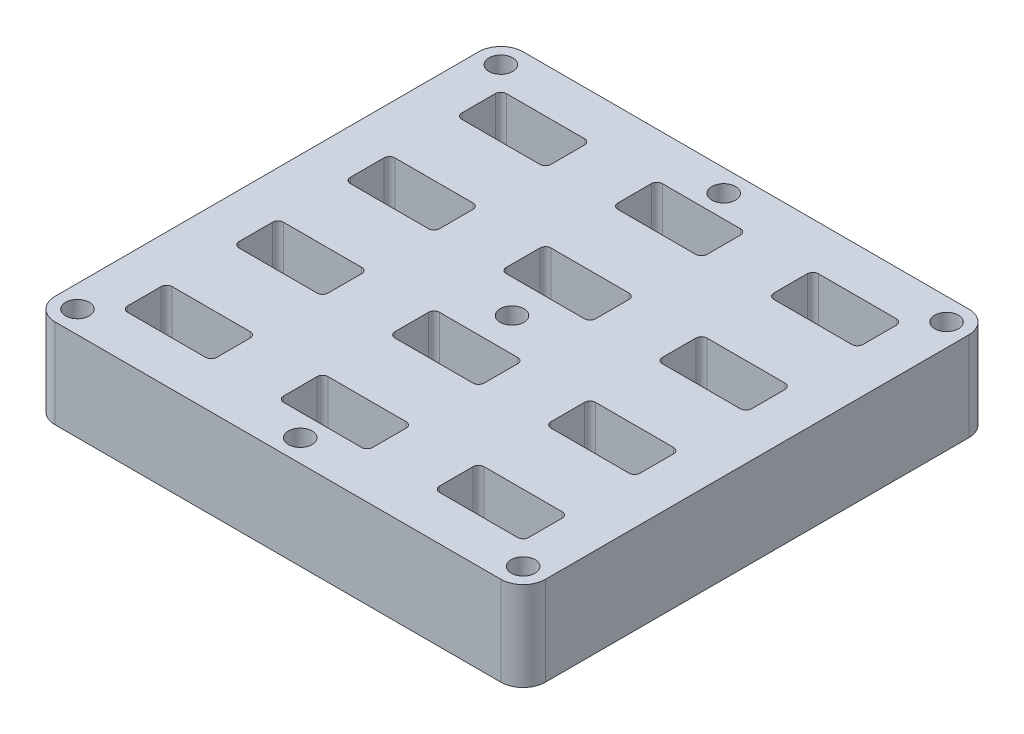
SolidWorks part; units mm, degrees
material "1060 Alloy"
ref_plane "Front" through (0, 0, 0) normal (0, 0, 1) x (1, 0, 0)
ref_plane "Top" through (0, 0, 0) normal (0, 1, 0) x (1, 0, 0)
ref_plane "Right" through (0, 0, 0) normal (1, 0, 0) x (0, 0, -1)
sketch "Sketch1" plane through (0, 0, 0) normal (0, 1, 0) x (1, 0, 0)
  line L1 (-63.5, -66.675) -> (63.5, -66.675)
  line L2 (-69.85, -60.325) -> (-69.85, 60.325)
  line L3 (-63.5, 66.675) -> (63.5, 66.675)
  line L4 (69.85, -60.325) -> (69.85, 60.325)
  line L5 (-69.85, -66.675) -> (69.85, 66.675) construction
  line L6 (-69.85, 66.675) -> (69.85, -66.675) construction
  line L7 (-55.5625, 41.275) -> (-33.3375, 41.275)
  line L8 (-57.15, 42.8625) -> (-57.15, 52.3875)
  line L9 (-55.5625, 53.975) -> (-33.3375, 53.975)
  line L10 (-31.75, 42.8625) -> (-31.75, 52.3875)
  line L11 (-57.15, 41.275) -> (-31.75, 53.975) construction
  line L12 (-57.15, 53.975) -> (-31.75, 41.275) construction
  line L16 (-12.7, 42.8625) -> (-12.7, 52.3875)
  line L17 (-11.1125, 41.275) -> (11.1125, 41.275)
  line L22 (12.7, 42.8625) -> (12.7, 52.3875)
  line L23 (-11.1125, 53.975) -> (11.1125, 53.975)
  line L28 (31.75, 42.8625) -> (31.75, 52.3875)
  line L29 (33.3375, 41.275) -> (55.5625, 41.275)
  line L110 (57.15, 42.8625) -> (57.15, 52.3875)
  line L111 (33.3375, 53.975) -> (55.5625, 53.975)
  line L196 (-57.15, 11.1125) -> (-57.15, 20.6375)
  line L197 (-55.5625, 9.525) -> (-33.3375, 9.525)
  line L198 (-31.75, 11.1125) -> (-31.75, 20.6375)
  line L199 (-55.5625, 22.225) -> (-33.3375, 22.225)
  line L200 (-12.7, 11.1125) -> (-12.7, 20.6375)
  line L201 (-11.1125, 22.225) -> (11.1125, 22.225)
  line L202 (12.7, 11.1125) -> (12.7, 20.6375)
  line L203 (-11.1125, 9.525) -> (11.1125, 9.525)
  line L204 (31.75, 11.1125) -> (31.75, 20.6375)
  line L205 (33.3375, 22.225) -> (55.5625, 22.225)
  line L206 (57.15, 11.1125) -> (57.15, 20.6375)
  line L207 (33.3375, 9.525) -> (55.5625, 9.525)
  line L212 (-57.15, -20.6375) -> (-57.15, -11.1125)
  line L213 (-55.5625, -22.225) -> (-33.3375, -22.225)
  line L214 (-31.75, -20.6375) -> (-31.75, -11.1125)
  line L215 (-55.5625, -9.525) -> (-33.3375, -9.525)
  line L216 (-12.7, -20.6375) -> (-12.7, -11.1125)
  line L217 (-11.1125, -9.525) -> (11.1125, -9.525)
  line L218 (12.7, -20.6375) -> (12.7, -11.1125)
  line L219 (-11.1125, -22.225) -> (11.1125, -22.225)
  line L220 (31.75, -20.6375) -> (31.75, -11.1125)
  line L221 (33.3375, -9.525) -> (55.5625, -9.525)
  line L222 (57.15, -20.6375) -> (57.15, -11.1125)
  line L223 (33.3375, -22.225) -> (55.5625, -22.225)
  line L228 (-57.15, -52.3875) -> (-57.15, -42.8625)
  line L229 (-55.5625, -53.975) -> (-33.3375, -53.975)
  line L230 (-31.75, -52.3875) -> (-31.75, -42.8625)
  line L231 (-55.5625, -41.275) -> (-33.3375, -41.275)
  line L232 (-12.7, -52.3875) -> (-12.7, -42.8625)
  line L233 (-11.1125, -41.275) -> (11.1125, -41.275)
  line L234 (12.7, -52.3875) -> (12.7, -42.8625)
  line L235 (-11.1125, -53.975) -> (11.1125, -53.975)
  line L236 (31.75, -52.3875) -> (31.75, -42.8625)
  line L237 (33.3375, -41.275) -> (55.5625, -41.275)
  line L238 (57.15, -52.3875) -> (57.15, -42.8625)
  line L239 (33.3375, -53.975) -> (55.5625, -53.975)
  arc A0 (-55.5625, 41.275) -> (-57.15, 42.8625) centre (-55.5625, 42.8625) cw
  arc A1 (-33.3375, 41.275) -> (-31.75, 42.8625) centre (-33.3375, 42.8625) ccw
  arc A2 (-33.3375, 53.975) -> (-31.75, 52.3875) centre (-33.3375, 52.3875) cw
  arc A3 (-55.5625, 53.975) -> (-57.15, 52.3875) centre (-55.5625, 52.3875) ccw
  arc A4 (-11.1125, 53.975) -> (-12.7, 52.3875) centre (-11.1125, 52.3875) ccw
  arc A5 (-11.1125, 41.275) -> (-12.7, 42.8625) centre (-11.1125, 42.8625) cw
  arc A6 (11.1125, 41.275) -> (12.7, 42.8625) centre (11.1125, 42.8625) ccw
  arc A7 (11.1125, 53.975) -> (12.7, 52.3875) centre (11.1125, 52.3875) cw
  arc A8 (33.3375, 53.975) -> (31.75, 52.3875) centre (33.3375, 52.3875) ccw
  arc A9 (33.3375, 41.275) -> (31.75, 42.8625) centre (33.3375, 42.8625) cw
  arc A10 (55.5625, 41.275) -> (57.15, 42.8625) centre (55.5625, 42.8625) ccw
  arc A11 (55.5625, 53.975) -> (57.15, 52.3875) centre (55.5625, 52.3875) cw
  arc A96 (-55.5625, 22.225) -> (-57.15, 20.6375) centre (-55.5625, 20.6375) ccw
  arc A97 (-55.5625, 9.525) -> (-57.15, 11.1125) centre (-55.5625, 11.1125) cw
  arc A98 (-33.3375, 9.525) -> (-31.75, 11.1125) centre (-33.3375, 11.1125) ccw
  arc A99 (-33.3375, 22.225) -> (-31.75, 20.6375) centre (-33.3375, 20.6375) cw
  arc A100 (-11.1125, 22.225) -> (-12.7, 20.6375) centre (-11.1125, 20.6375) ccw
  arc A101 (11.1125, 22.225) -> (12.7, 20.6375) centre (11.1125, 20.6375) cw
  arc A102 (11.1125, 9.525) -> (12.7, 11.1125) centre (11.1125, 11.1125) ccw
  arc A103 (-11.1125, 9.525) -> (-12.7, 11.1125) centre (-11.1125, 11.1125) cw
  arc A104 (33.3375, 22.225) -> (31.75, 20.6375) centre (33.3375, 20.6375) ccw
  arc A105 (55.5625, 22.225) -> (57.15, 20.6375) centre (55.5625, 20.6375) cw
  arc A106 (55.5625, 9.525) -> (57.15, 11.1125) centre (55.5625, 11.1125) ccw
  arc A107 (33.3375, 9.525) -> (31.75, 11.1125) centre (33.3375, 11.1125) cw
  arc A112 (-55.5625, -9.525) -> (-57.15, -11.1125) centre (-55.5625, -11.1125) ccw
  arc A113 (-55.5625, -22.225) -> (-57.15, -20.6375) centre (-55.5625, -20.6375) cw
  arc A114 (-33.3375, -22.225) -> (-31.75, -20.6375) centre (-33.3375, -20.6375) ccw
  arc A115 (-33.3375, -9.525) -> (-31.75, -11.1125) centre (-33.3375, -11.1125) cw
  arc A116 (-11.1125, -9.525) -> (-12.7, -11.1125) centre (-11.1125, -11.1125) ccw
  arc A117 (11.1125, -9.525) -> (12.7, -11.1125) centre (11.1125, -11.1125) cw
  arc A118 (11.1125, -22.225) -> (12.7, -20.6375) centre (11.1125, -20.6375) ccw
  arc A119 (-11.1125, -22.225) -> (-12.7, -20.6375) centre (-11.1125, -20.6375) cw
  arc A120 (33.3375, -9.525) -> (31.75, -11.1125) centre (33.3375, -11.1125) ccw
  arc A121 (55.5625, -9.525) -> (57.15, -11.1125) centre (55.5625, -11.1125) cw
  arc A122 (55.5625, -22.225) -> (57.15, -20.6375) centre (55.5625, -20.6375) ccw
  arc A123 (33.3375, -22.225) -> (31.75, -20.6375) centre (33.3375, -20.6375) cw
  arc A128 (-55.5625, -41.275) -> (-57.15, -42.8625) centre (-55.5625, -42.8625) ccw
  arc A129 (-55.5625, -53.975) -> (-57.15, -52.3875) centre (-55.5625, -52.3875) cw
  arc A130 (-33.3375, -53.975) -> (-31.75, -52.3875) centre (-33.3375, -52.3875) ccw
  arc A131 (-33.3375, -41.275) -> (-31.75, -42.8625) centre (-33.3375, -42.8625) cw
  arc A132 (-11.1125, -41.275) -> (-12.7, -42.8625) centre (-11.1125, -42.8625) ccw
  arc A133 (11.1125, -41.275) -> (12.7, -42.8625) centre (11.1125, -42.8625) cw
  arc A134 (11.1125, -53.975) -> (12.7, -52.3875) centre (11.1125, -52.3875) ccw
  arc A135 (-11.1125, -53.975) -> (-12.7, -52.3875) centre (-11.1125, -52.3875) cw
  arc A136 (33.3375, -41.275) -> (31.75, -42.8625) centre (33.3375, -42.8625) ccw
  arc A137 (55.5625, -41.275) -> (57.15, -42.8625) centre (55.5625, -42.8625) cw
  arc A138 (55.5625, -53.975) -> (57.15, -52.3875) centre (55.5625, -52.3875) ccw
  arc A139 (33.3375, -53.975) -> (31.75, -52.3875) centre (33.3375, -52.3875) cw
  arc A176 (69.85, 60.325) -> (63.5, 66.675) centre (63.5, 60.325) ccw
  arc A177 (69.85, -60.325) -> (63.5, -66.675) centre (63.5, -60.325) cw
  arc A178 (-63.5, -66.675) -> (-69.85, -60.325) centre (-63.5, -60.325) cw
  arc A179 (-69.85, 60.325) -> (-63.5, 66.675) centre (-63.5, 60.325) cw
  point P0 (0, 0)
  point P6 (-44.45, 47.625)
  dimension "D11" = 1.5875
  dimension "D12" = 6.35
  dimension "D1" = 139.7
  dimension "D2" = 133.35
  dimension "D3" = 25.4
  dimension "D4" = 12.7
  dimension "D6" = 12.7
  dimension "D7" = 19.05
  dimension "D8" = 12.7
  dimension "D10" = 19.05
  dimension "D5" = 3
  dimension "D9" = 4
extrude "Boss-Extrude1" add sketch "Sketch1" along normal blind 25.4
hole_wizard "1/4 Clearance Hole1" positions "3DSketch1" profile "Sketch2" hole size "1/4" standard "ANSI Inch" end condition through all
sketch3d "3DSketch1"
  line L1 (-63.5, 25.4, 60.325) -> (-63.5, 25.4, -60.325) construction
  line L2 (-63.5, 25.4, 60.325) -> (63.5, 25.4, 60.325) construction
  line L3 (63.5, 25.4, 60.325) -> (63.5, 25.4, -60.325) construction
  line L4 (-63.5, 25.4, -60.325) -> (63.5, 25.4, -60.325) construction
  line L5 (-63.5, 25.4, 60.325) -> (63.5, 25.4, -60.325) construction
  line L6 (63.5, 25.4, 60.325) -> (-63.5, 25.4, -60.325) construction
  line L15 (-57.15, 25.4, -47.625) -> (-69.85, 25.4, -47.625) construction
  line L16 (-57.15, 25.4, -52.3875) -> (-57.15, 25.4, -42.8625) construction
  line L17 (-69.85, 25.4, -60.325) -> (-69.85, 25.4, 60.325) construction
  line L19 (-44.45, 25.4, -53.975) -> (-44.45, 25.4, -66.675) construction
  line L20 (-33.3375, 25.4, -53.975) -> (-55.5625, 25.4, -53.975) construction
  line L21 (63.5, 25.4, -66.675) -> (-63.5, 25.4, -66.675) construction
  point P0 (-63.5, 25.4, -60.325)
  point P2 (63.5, 25.4, -60.325)
  point P7 (63.5, 25.4, 60.325)
  point P10 (-63.5, 25.4, 60.325)
  point P12 (0, 25.4, 0)
  point P13 (0, 25.4, 0)
  point P106 (0, 25.4, -60.325)
  point P108 (0, 25.4, 60.325)
  point P111 (0, 25.4, 60.325)
  point P113 (0, 25.4, -60.325)
  point P146 (-63.5, 25.4, -47.625)
  point P147 (-44.45, 25.4, -60.325)
sketch "Sketch2" plane through (-63.5, 25.4, -60.325) normal (1, 0, 0) x (0, 0, 1)
  line L0 (0, 0) -> (0, 25.4)
  line L1 (0, 25.4) -> (3.3782, 25.4)
  line L2 (3.3782, 25.4) -> (3.3782, 0)
  line L5 (3.3782, 0) -> (0, 0)
  line L11 (0, -6.35) -> (0, 107.95) construction
  dimension "Thru Hole Dia." = 6.7564
  dimension "Thru Hole Depth" = 25.4
